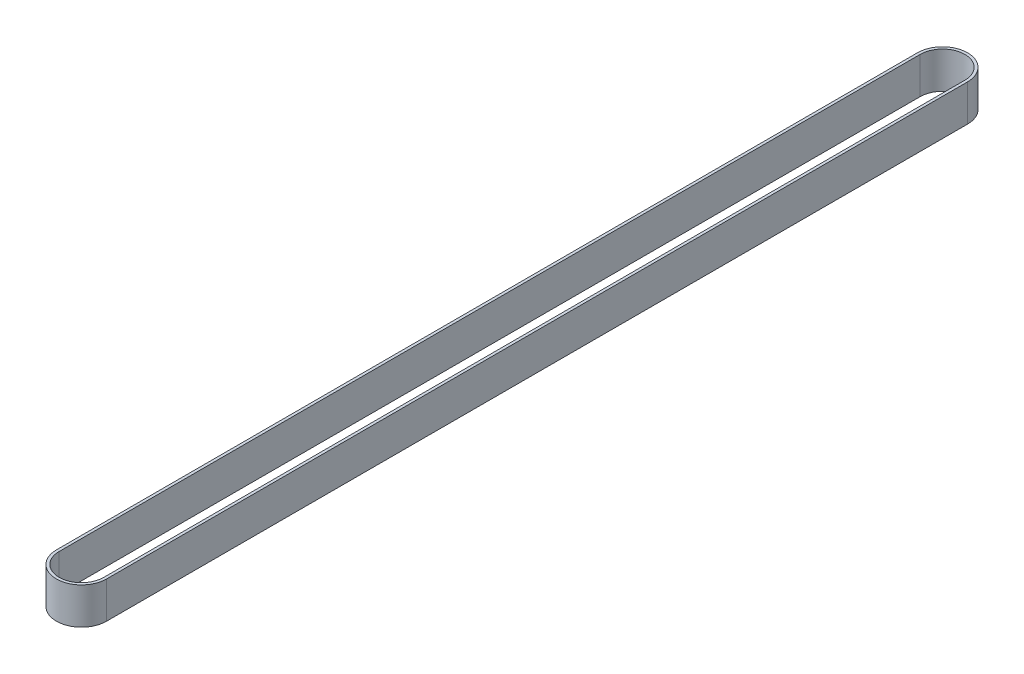
SolidWorks part; units mm, degrees
material "天然橡胶"
ref_plane "前视基准面" through (0, 0, 0) normal (0, 0, 1) x (1, 0, 0)
ref_plane "上视基准面" through (0, 0, 0) normal (0, 1, 0) x (1, 0, 0)
ref_plane "右视基准面" through (0, 0, 0) normal (1, 0, 0) x (0, 0, -1)
other "Configuration Table"
sketch "草图1" plane through (0, 0, 0) normal (0, 1, 0) x (1, 0, 0)
  line L0 (0, -117.55) -> (0, 117.55) construction
  line L1 (-6.86, -117.55) -> (-6.86, 117.55)
  line L2 (6.86, -117.55) -> (6.86, 117.55)
  line L3 (0, -117.55) -> (0, 117.55) construction
  line L4 (-6.11, -117.55) -> (-6.11, 117.55)
  line L5 (6.11, -117.55) -> (6.11, 117.55)
  arc A0 (-6.86, -117.55) -> (6.86, -117.55) centre (0, -117.55) ccw
  arc A1 (6.86, 117.55) -> (-6.86, 117.55) centre (0, 117.55) ccw
  arc A2 (-6.11, -117.55) -> (6.11, -117.55) centre (0, -117.55) ccw
  arc A3 (6.11, 117.55) -> (-6.11, 117.55) centre (0, 117.55) ccw
  point P2 (0, 0)
  point P9 (0, 0)
  dimension "D3" = 6.11
  dimension "D4" = 6.86
  dimension "D1" = 235.1
  dimension "D2" = 235.1
extrude "凸台-拉伸1" add sketch "草图1" along normal blind 10
